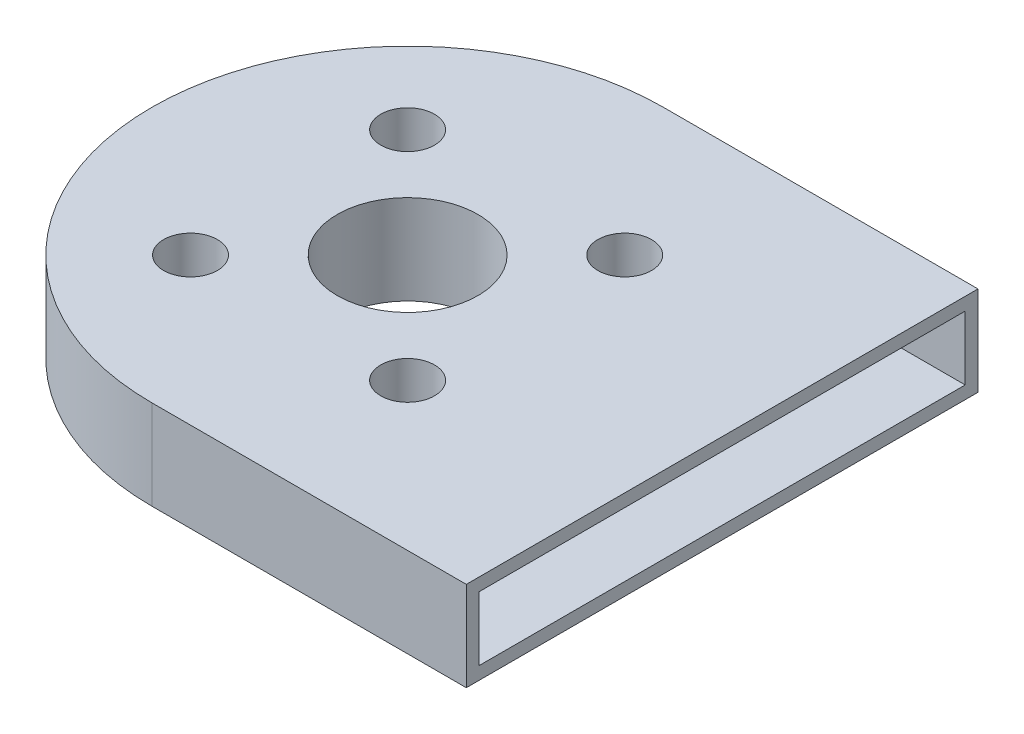
SolidWorks part; units mm, degrees
ref_plane "Front Plane" through (0, 0, 0) normal (0, 0, 1) x (1, 0, 0)
ref_plane "Top Plane" through (0, 0, 0) normal (0, 1, 0) x (1, 0, 0)
ref_plane "Right Plane" through (0, 0, 0) normal (1, 0, 0) x (0, 0, -1)
sketch "Sketch1" plane through (0, 0, 0) normal (0, 1, 0) x (1, 0, 0)
  circle A0 centre (0, 0) radius 10
  circle A1 centre (0, 0) radius 2.75
  circle A2 centre (-4.2426, 4.2426) radius 0.1883
  circle A3 centre (-4.2426, 4.2426) radius 1.05
  point P7 (0, 0)
  dimension "D1" = 20
  dimension "D2" = 5.5
  dimension "D3" = 2.1
  dimension "D5" = 0.3765
  dimension "D6" = 4.2426
  dimension "D4" = 4.2426
extrude "Boss-Extrude1" add sketch "Sketch1" along normal blind 3.5 contours A0 A3 A1
sketch "Sketch8" plane through (0, 3.5, 0) normal (0, 1, 0) x (1, 0, 0)
  circle A0 centre (-4.2426, -4.2426) radius 1.05
  circle A1 centre (4.2426, 4.2426) radius 1.05
  circle A3 centre (4.2426, -4.2426) radius 1.05
  dimension "D1" = 2.1
  dimension "D2" = 2.1
  dimension "D3" = 2.1
extrude "Cut-Extrude2" cut sketch "Sketch8" against normal blind 10
sketch "Sketch11" plane through (0, 0, 0) normal (0, -1, 0) x (1, 0, 0)
  line L0 (0, 10) -> (12.2939, 10)
  line L1 (0, -10) -> (12.2939, -10)
  line L2 (12.2939, 10) -> (12.2939, -10)
  circle A0 centre (0, 0) radius 10 construction
  circle A2 centre (0, 0) radius 10
  arc A3 (0, 10) -> (0, -10) centre (0, 0) ccw
  circle M6 centre (0, 0) radius 10
  dimension "D1" = 0
extrude "Boss-Extrude5" add sketch "Sketch11" against normal blind 3.5 contours L2 L0 L1 M6
shell "Shell2" thickness 0.5
